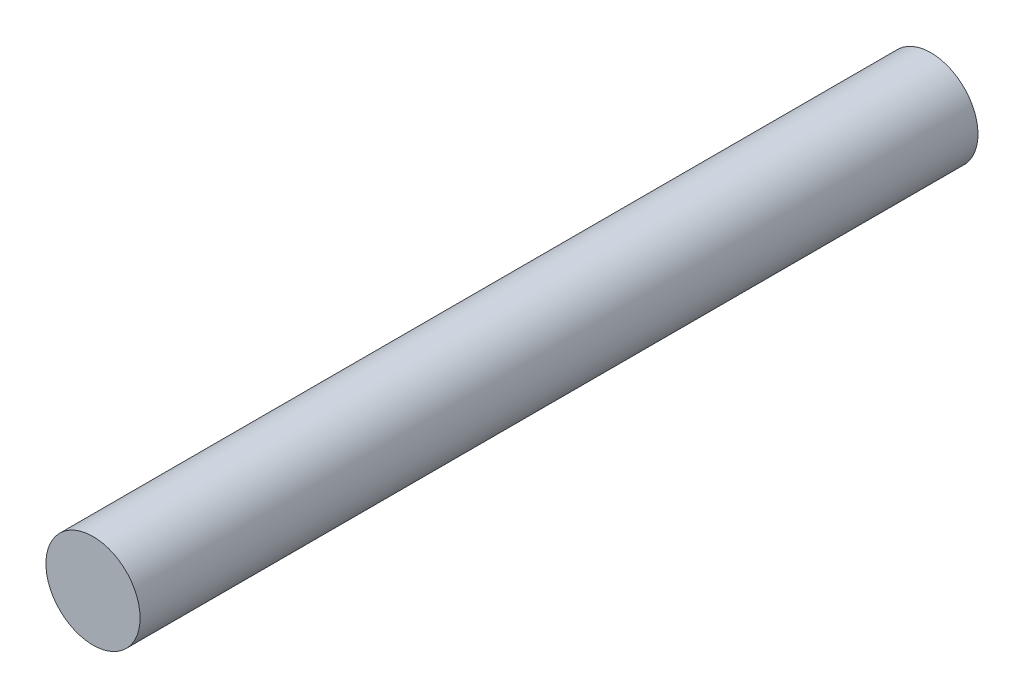
SolidWorks part; units mm, degrees
ref_plane "Front Plane" through (0, 0, 0) normal (0, 0, 1) x (1, 0, 0)
ref_plane "Top Plane" through (0, 0, 0) normal (0, 1, 0) x (1, 0, 0)
ref_plane "Right Plane" through (0, 0, 0) normal (1, 0, 0) x (0, 0, -1)
sketch "Sketch1" plane through (0, 0, 0) normal (0, 0, 1) x (1, 0, 0)
  circle A0 centre (0, 0) radius 3.4
  dimension "D1" = 6.8
extrude "Boss-Extrude1" add sketch "Sketch1" along normal mid plane 60.5
